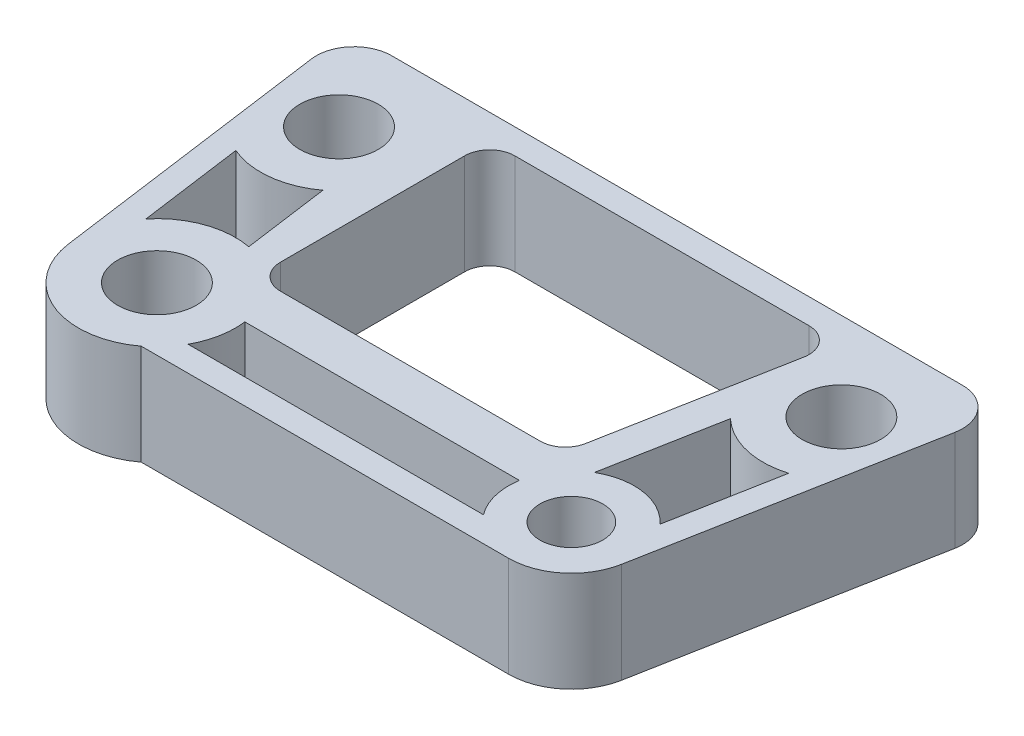
SolidWorks part; units mm, degrees
material "7075-T6 (SN)"
ref_plane "X-Y Datum" through (0, 0, 0) normal (0, 0, 1) x (1, 0, 0)
ref_plane "X-Z Datum" through (0, 0, 0) normal (0, 1, 0) x (1, 0, 0)
ref_plane "Y-Z Datum" through (0, 0, 0) normal (1, 0, 0) x (0, 0, -1)
sketch "Sketch1" plane through (0, 0, 0) normal (0, 1, 0) x (1, 0, 0)
  line L1 (54.2925, 13.97) -> (-12.3825, 13.97) construction
  line L4 (54.2925, 31.75) -> (-12.3825, 31.75)
  line L6 (46.355, 22.86) -> (-4.445, 22.86) construction
  line L7 (54.2925, 31.75) -> (54.2925, 13.97)
  line L8 (-12.3825, 31.75) -> (-12.3825, 13.97)
  line L21 (-7.9375, 0) -> (-12.3825, 13.97)
  line L22 (6.264, 8.509) -> (16.764, 8.509) construction
  line L24 (16.764, 8.509) -> (27.264, 8.509) construction
  line L25 (7.0861, -3.5764) -> (36.6629, -3.5764)
  line L27 (48.26, 0) -> (54.2925, 13.97)
  circle A0 centre (0, 0) radius 3.9688
  circle A1 centre (41.91, 0) radius 3.175
  circle A2 centre (46.355, 22.86) radius 3.9688
  circle A3 centre (-4.445, 22.86) radius 3.9687
  arc A5 (7.0861, -3.5764) -> (-7.9375, 0) centre (0, 0) cw
  circle A7 centre (16.764, 8.509) radius 5.3
  circle A8 centre (6.264, 8.509) radius 1.5
  circle A9 centre (27.264, 8.509) radius 1.5
  arc A10 (36.6629, -3.5764) -> (48.26, 0) centre (41.91, 0) ccw
  dimension "D2" = 6.35
  dimension "D7" = 7.9375
  dimension "D8" = 6.35
  dimension "D12" = 10.6
  dimension "D10" = 7.9375
  dimension "D17" = 3
  dimension "D19" = 7.9375
  dimension "D18" = 7.9375
  dimension "D3" = 50.8
  dimension "D4" = 17.78
  dimension "D5" = 8.89
  dimension "D6" = 31.75
  dimension "D9" = 4.445
  dimension "D11" = 7.9375
  dimension "D13" = 16.764
  dimension "D14" = 5.461
  dimension "D16" = 10.5
  dimension "D20" = 41.91
extrude "Boss-Extrude1" [suppressed] add sketch "Sketch1" against normal blind 10.16
sketch "Sketch3" [suppressed] plane through (0, 0, 0) normal (0, 1, 0) x (1, 0, 0)
  line L0 (0, 0) -> (0, -44.5462) construction
  line L1 (0, 0) -> (26.3151, -45.579) construction
  dimension "D1" = 30
other "Graphic1"
other "Graphic (Closed) -1"
other "Graphic2"
other "Graphic (Closed) -2"
sketch "Sketch4" plane through (0, 0, 0) normal (0, 1, 0) x (1, 0, 0)
  line L0 (36.7305, 29.21) -> (6.985, 29.21)
  line L1 (54.2925, 31.75) -> (-12.3825, 31.75)
  line L7 (46.355, 22.86) -> (-4.445, 22.86) construction
  line L8 (-4.445, 22.86) -> (-12.3825, 22.86) construction
  line L9 (54.2925, 13.97) -> (-12.3825, 13.97) construction
  line L17 (-12.3825, 31.75) -> (-7.8634, -1.0823)
  line L19 (48.1523, -1.1645) -> (54.2925, 31.75)
  line L25 (4.445, 26.67) -> (4.445, 8.0433)
  line L27 (35.7526, 7.5775) -> (39.2274, 26.2042)
  line L28 (46.587, 4.2951) -> (48.6317, 15.256)
  line L29 (38.7374, 5.5007) -> (40.9001, 17.0939)
  line L30 (36.83, -3.81) -> (6.9633, -3.81)
  line L31 (35.6418, 1.016) -> (7.8722, 1.016)
  line L32 (-6.1407, 5.0295) -> (-7.5919, 15.573)
  line L33 (1.4909, 7.7962) -> (0.2939, 16.4924)
  line L35 (33.2557, 5.5033) -> (6.985, 5.5033)
  line L39 (41.91, -6.35) -> (4.7625, -6.35)
  circle A0 centre (0, 0) radius 3.9688
  circle A1 centre (46.355, 22.86) radius 3.9687
  circle A2 centre (-4.445, 22.86) radius 3.9688
  circle A6 centre (41.91, 0) radius 3.175
  arc A15 (-7.8634, -1.0823) -> (4.7625, -6.35) centre (0, 0) ccw
  arc A16 (41.91, -6.35) -> (48.1523, -1.1645) centre (41.91, 0) ccw
  arc A17 (36.7305, 29.21) -> (39.2274, 26.2042) centre (36.7305, 26.67) cw
  arc A18 (4.445, 26.67) -> (6.985, 29.21) centre (6.985, 26.67) cw
  arc A21 (46.587, 4.2951) -> (38.7374, 5.5007) centre (41.91, 0) ccw
  arc A22 (48.6317, 15.256) -> (40.9001, 17.0939) centre (46.355, 22.86) cw
  arc A23 (36.83, -3.81) -> (35.6418, 1.016) centre (41.91, 0) cw
  arc A24 (6.9633, -3.81) -> (7.8722, 1.016) centre (0, 0) ccw
  arc A25 (-6.1407, 5.0295) -> (1.4909, 7.7962) centre (0, 0) cw
  arc A26 (-7.5919, 15.573) -> (0.2939, 16.4924) centre (-4.445, 22.86) ccw
  arc A27 (4.445, 8.0433) -> (6.985, 5.5033) centre (6.985, 8.0433) ccw
  arc A28 (33.2557, 5.5033) -> (35.7526, 7.5775) centre (33.2557, 8.0433) ccw
  point P28 (39.7881, 29.21)
  point P33 (4.445, 29.21)
  dimension "D1" = 7.9375
  dimension "D2" = 7.9375
  dimension "D3" = 6.35
  dimension "D4" = 8.4667
  dimension "D5" = 4.4873
  dimension "D27" = 7.9375
  dimension "D29" = 6.35
  dimension "D30" = 7.9375
  dimension "D35" = 7.9375
  dimension "D36" = 2.54
  dimension "D22" = 2.54
  dimension "D24" = 7.9375
  dimension "D25" = 6.35
  dimension "D26" = 6.35
  dimension "D33" = 7.9375
  dimension "D34" = 7.9375
  dimension "D7" = 22.86
  dimension "D8" = 50.8
  dimension "D9" = 7.9375
  dimension "D10" = 4.445
  dimension "D13" = 41.91
  dimension "D14" = 17.78
  dimension "D15" = 8.89
  dimension "D16" = 7.9375
  dimension "D18" = 2.54
  dimension "D19" = 7.62
  dimension "D20" = 2.54
  dimension "D23" = 2.54
  dimension "D31" = 8.89
  dimension "D32" = 7.9375
extrude "Boss-Extrude2" add sketch "Sketch4" along normal blind 10.16
ref_point "Point1"
ref_point "Point2"
sketch "Sketch5" plane through (0, 10.16, 0) normal (0, 1, 0) x (1, 0, 0)
  line L0 (0, 0) -> (0, -25.3617) construction
  line L1 (0, 0) -> (11.466, -19.8596) construction
  dimension "D1" = 30
fillet "Fillet1" radius 3.81 2 edges at (-12.3825, 5.08, -31.75) (54.2925, 5.08, -31.75)
